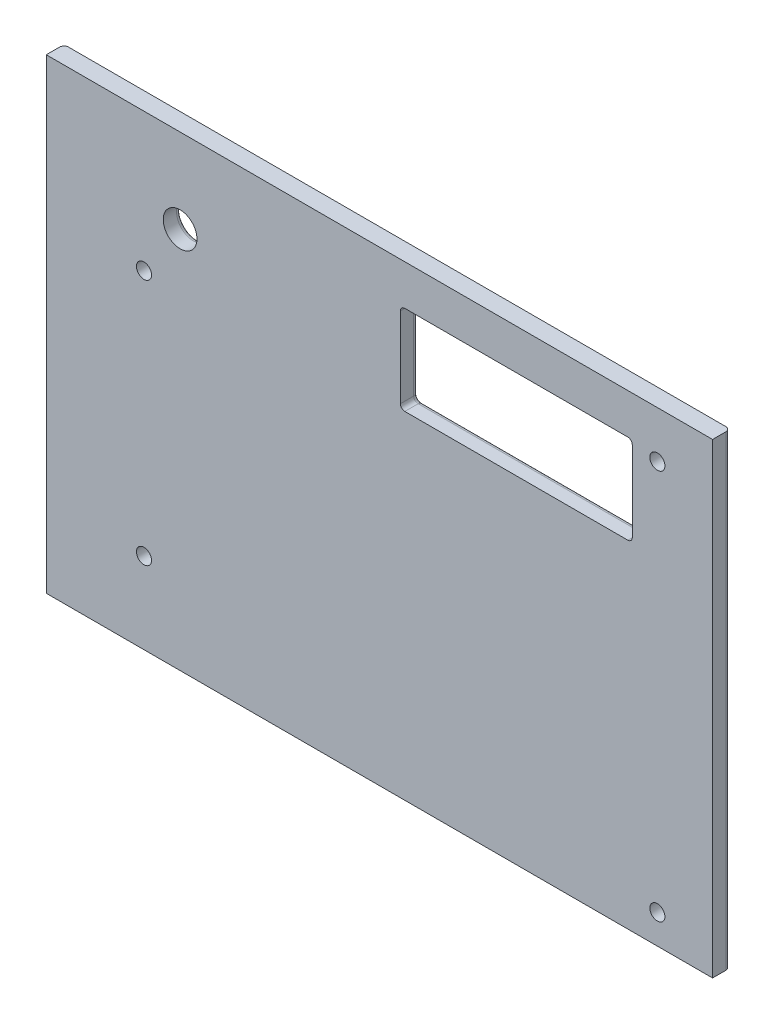
SolidWorks part; units mm, degrees
ref_plane "Front Plane" through (0, 0, 0) normal (0, 0, 1) x (1, 0, 0)
ref_plane "Top Plane" through (0, 0, 0) normal (0, 1, 0) x (1, 0, 0)
ref_plane "Right Plane" through (0, 0, 0) normal (1, 0, 0) x (0, 0, -1)
sketch "Sketch1" plane through (0, 0, 0) normal (0, 0, 1) x (1, 0, 0)
  line L1 (75, 52.5) -> (-75, 52.5)
  line L2 (75, 52.5) -> (75, -52.5)
  line L3 (75, -52.5) -> (-75, -52.5)
  line L4 (-75, 52.5) -> (-75, -52.5)
  line L5 (75, 52.5) -> (-75, -52.5) construction
  line L6 (75, -52.5) -> (-75, 52.5) construction
  point P0 (0, 0)
  dimension "D1" = 105
  dimension "D2" = 150
extrude "Boss-Extrude1" add sketch "Sketch1" along normal mid plane 4
hole_wizard "M3 Clearance Hole1" positions "Sketch2" profile "Sketch3" hole size "M3" standard "ISO" end condition through all
sketch "Sketch2" plane through (0, 0, 2) normal (0, 0, 1) x (1, 0, 0)
  line L3 (-75, 52.5) -> (-75, -52.5) construction
  line L4 (-75, -52.5) -> (75, -52.5) construction
  point P0 (-53, 21.4)
  point P2 (-53, -34.23)
  point P4 (62.57, -45.91)
  point P6 (62.57, 41.97)
  dimension "D1" = 55.63
  dimension "D2" = 87.88
  dimension "D3" = 115.57
  dimension "D4" = 22
  dimension "D5" = 18.27
  dimension "D6" = 6.59
sketch "Sketch3" plane through (-53, 21.4, 2) normal (1, 0, 0) x (0, -1, 0)
  line L0 (0, 0) -> (0, 4)
  line L1 (0, 4) -> (3.3, 4)
  line L2 (1.7, 2.4) -> (1.7, 0)
  line L5 (1.7, 0) -> (0, 0)
  line L7 (3.3, 4) -> (1.7, 2.4)
  line L8 (-3.3, 4) -> (-1.7, 2.4) construction
  line L11 (0, -6.35) -> (0, 107.95) construction
  dimension "Thru Hole Dia." = 3.4
  dimension "Thru Hole Depth" = 4
  dimension "Far C'Sink Dia." = 6.6
  dimension "Far C'Sink Angle" = 90
hole_wizard "M7 Clearance Hole1" positions "Sketch4" profile "Sketch5" hole size "M7" standard "ISO" end condition through all
sketch "Sketch4" plane through (0, 0, 2) normal (0, 0, 1) x (1, 0, 0)
  circle A0 centre (-53, 21.4) radius 1.7 construction
  point P0 (-44.87, 33.54)
  dimension "D1" = 8.13
  dimension "D2" = 12.14
sketch "Sketch5" plane through (-44.87, 33.54, 2) normal (1, 0, 0) x (0, -1, 0)
  line L0 (0, 0) -> (0, 4)
  line L1 (0, 4) -> (3.8, 4)
  line L2 (3.8, 4) -> (3.8, 0)
  line L5 (3.8, 0) -> (0, 0)
  line L11 (0, -6.35) -> (0, 107.95) construction
  dimension "Thru Hole Dia." = 7.6
  dimension "Thru Hole Depth" = 4
sketch "Sketch6" plane through (0, 0, 2) normal (0, 0, 1) x (1, 0, 0)
  line L1 (56.92, 43.42) -> (4.72, 43.42)
  line L2 (56.92, 43.42) -> (56.92, 23.32)
  line L3 (56.92, 23.32) -> (4.72, 23.32)
  line L4 (4.72, 43.42) -> (4.72, 23.32)
  circle A0 centre (62.57, 41.97) radius 1.7 construction
  dimension "D1" = 1.45
  dimension "D2" = 5.65
  dimension "D3" = 20.1
  dimension "D4" = 52.2
extrude "Cut-Extrude1" cut sketch "Sketch6" against normal blind 10 contours L2 L1 L4 L3
fillet "Fillet1" radius 1 8 edges at (56.92, 43.42, 0) (4.72, 43.42, 0) (56.92, 23.32, 0) (4.72, 23.32, 0) (4.72, 33.37, -2) (30.82, 23.32, -2) (30.82, 43.42, -2) (56.92, 33.37, -2)
fillet "Fillet2" radius 1 1 edges at (-41.07, 33.54, -2)
fillet "Fillet3" radius 1 2 edges at (-75, 0, -2) (75, 0, -2)
